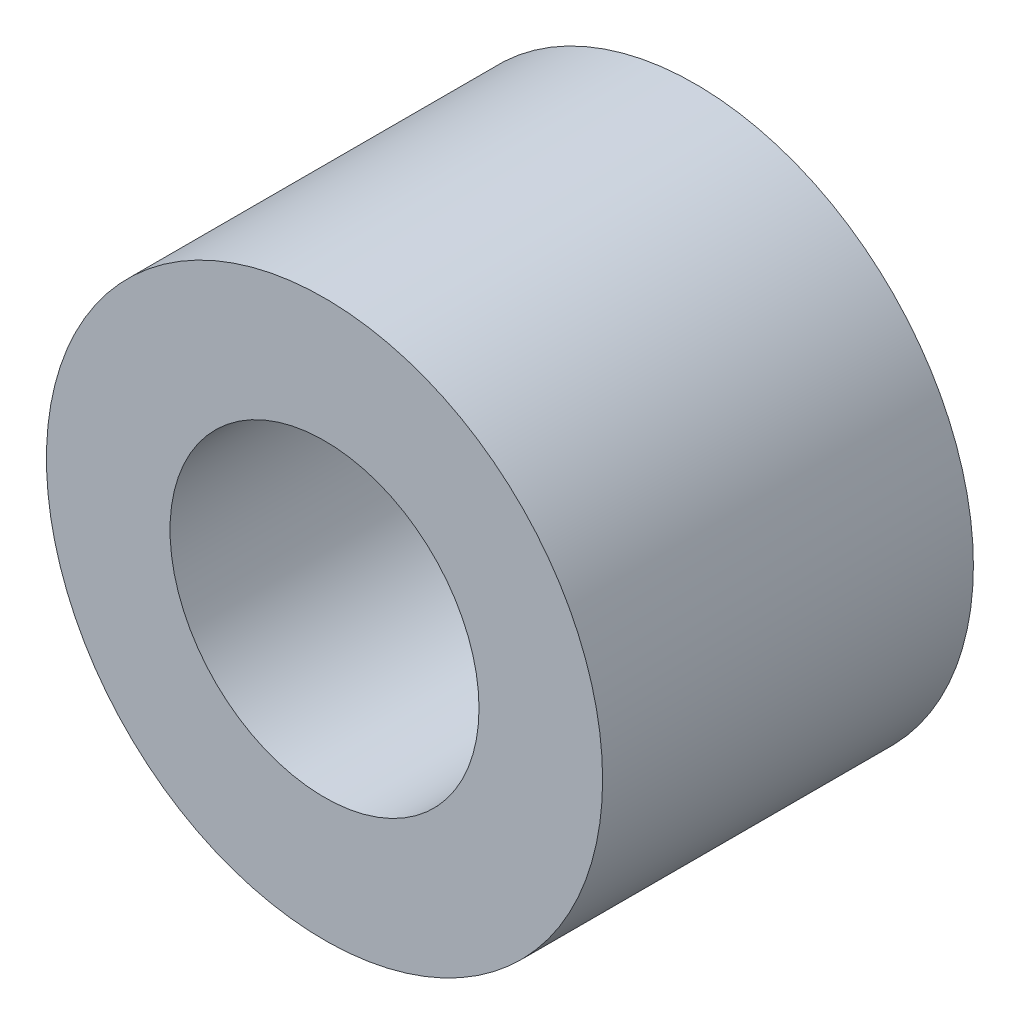
SolidWorks part; units mm, degrees
ref_plane "Plano frontal" through (0, 0, 0) normal (0, 0, 1) x (1, 0, 0)
ref_plane "Plano superior" through (0, 0, 0) normal (0, 1, 0) x (1, 0, 0)
ref_plane "Plano direito" through (0, 0, 0) normal (1, 0, 0) x (0, 0, -1)
sketch "Esboço1" plane through (0, 0, 0) normal (0, 0, 1) x (1, 0, 0)
  circle A0 centre (0, 0) radius 2.5
  circle A2 centre (0, 0) radius 4.5
  dimension "D1" = 5
  dimension "D2" = 2
extrude "Ressalto-extrusão1" add sketch "Esboço1" along normal blind 6
